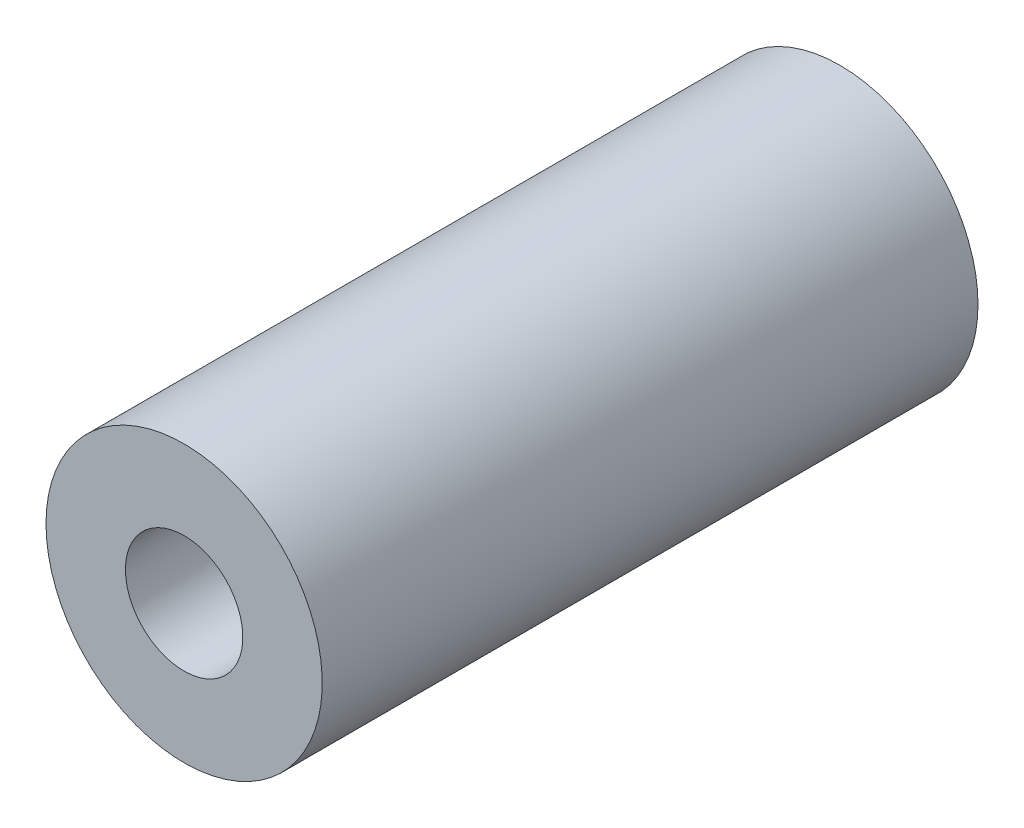
SolidWorks part; units mm, degrees
ref_plane "Front Plane" through (0, 0, 0) normal (0, 0, 1) x (1, 0, 0)
ref_plane "Top Plane" through (0, 0, 0) normal (0, 1, 0) x (1, 0, 0)
ref_plane "Right Plane" through (0, 0, 0) normal (1, 0, 0) x (0, 0, -1)
sketch "Sketch1" plane through (0, 0, 0) normal (0, 0, 1) x (1, 0, 0)
  circle A0 centre (0, 0) radius 0.85
  circle A1 centre (0, 0) radius 2
  dimension "D1" = 1.7
  dimension "D2" = 4
extrude "Boss-Extrude1" add sketch "Sketch1" along normal up to surface (9.496 mm away)
